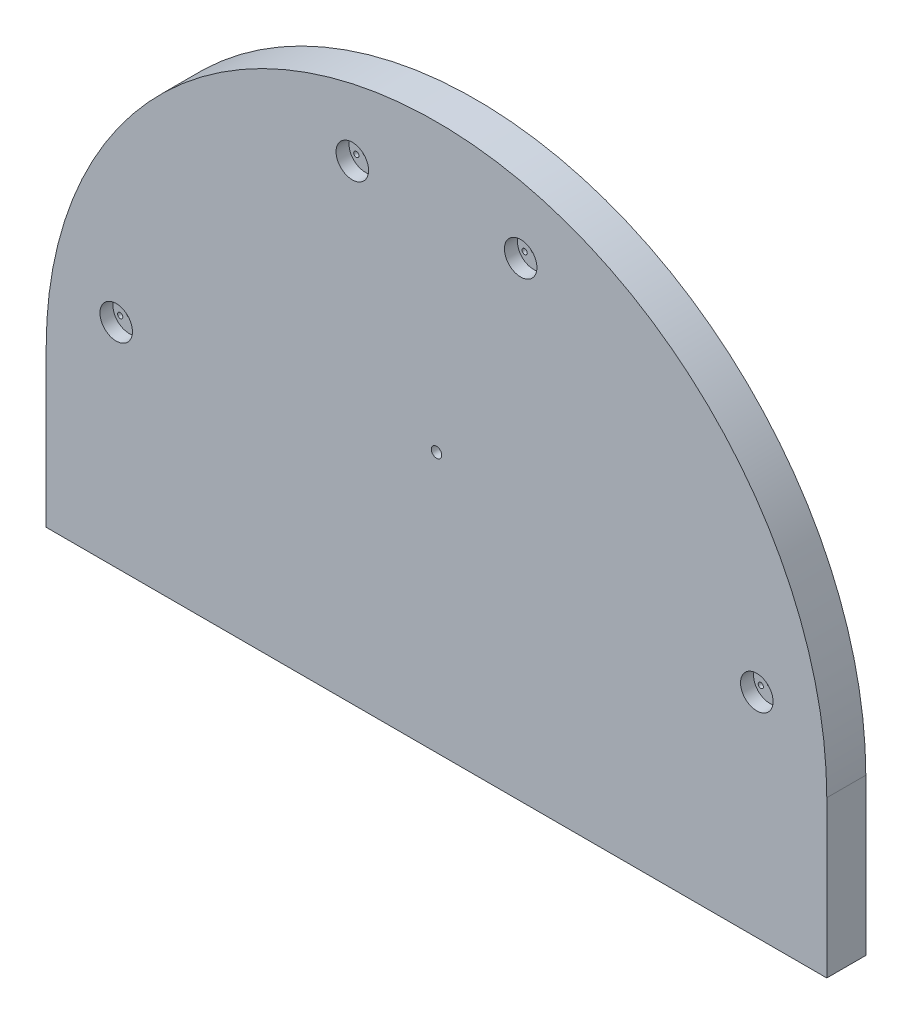
SolidWorks part; units mm, degrees
material "有机玻璃 (TM) GS 丙烯酸铸钣"
ref_plane "前视基准面" through (0, 0, 0) normal (0, 0, 1) x (1, 0, 0)
ref_plane "上视基准面" through (0, 0, 0) normal (0, 1, 0) x (1, 0, 0)
ref_plane "右视基准面" through (0, 0, 0) normal (1, 0, 0) x (0, 0, -1)
sketch "草图1" plane through (0, 0, 0) normal (0, 0, 1) x (1, 0, 0)
  line L0 (-300, 0) -> (-300, -120)
  line L1 (-300, -120) -> (300, -120)
  line L2 (300, -120) -> (300, 0)
  arc A0 (300, 0) -> (-300, 0) centre (0, 0) ccw
  dimension "D1" = 600
  dimension "D2" = 120
extrude "凸台-拉伸1" add sketch "草图1" along normal blind 30
sketch "草图2" plane through (0, 0, 30) normal (0, 0, 1) x (1, 0, 0)
  line L0 (0, 0) -> (-246.2019, 43.412) construction
  line L1 (0, 0) -> (-64.7048, 241.4815) construction
  line L2 (0, 0) -> (0, 96.9223) construction
  line L3 (0, 0) -> (-105.8449, 0) construction
  circle A0 centre (0, 0) radius 250 construction
  circle A1 centre (-246.2019, 43.412) radius 12.5
  circle A2 centre (-64.7048, 241.4815) radius 12.5
  circle A3 centre (246.2019, 43.412) radius 12.5
  circle A4 centre (64.7048, 241.4815) radius 12.5
  dimension "D1" = 500
  dimension "D4" = 25
  dimension "D5" = 25
  dimension "D2" = 15
  dimension "D3" = 10
extrude "切除-拉伸1" cut sketch "草图2" against normal blind 10
sketch "草图4" plane through (0, 0, 20) normal (0, 0, 1) x (1, 0, 0)
  line L0 (0, 0) -> (0, 96.5541) construction
  line L1 (-246.2019, 51.412) -> (-253.1301, 39.412) construction
  line L2 (-246.2019, 51.412) -> (-246.2019, 43.412) construction
  line L3 (-246.2019, 51.412) -> (-239.2737, 39.412) construction
  line L4 (-64.7048, 249.4815) -> (-64.7048, 241.4815) construction
  line L5 (-64.7048, 241.4815) -> (-71.633, 237.4815) construction
  line L6 (-64.7048, 241.4815) -> (-57.7766, 237.4815) construction
  line L7 (64.7048, 241.4815) -> (57.7766, 237.4815) construction
  line L8 (64.7048, 241.4815) -> (71.633, 237.4815) construction
  line L9 (64.7048, 249.4815) -> (64.7048, 241.4815) construction
  line L10 (246.2019, 51.412) -> (239.2737, 39.412) construction
  line L11 (246.2019, 51.412) -> (246.2019, 43.412) construction
  line L12 (246.2019, 51.412) -> (253.1301, 39.412) construction
  circle A0 centre (-246.2019, 43.412) radius 2
  circle A4 centre (-246.2019, 43.412) radius 8 construction
  circle A5 centre (-246.2019, 51.412) radius 2
  circle A6 centre (-253.1301, 39.412) radius 2
  circle A7 centre (-239.2737, 39.412) radius 2
  circle A8 centre (0, 0) radius 250 construction
  circle A9 centre (-64.7048, 241.4815) radius 8 construction
  circle A10 centre (-64.7048, 249.4815) radius 2
  circle A11 centre (-71.633, 237.4815) radius 2
  circle A12 centre (-57.7766, 237.4815) radius 2
  circle A13 centre (-64.7048, 241.4815) radius 2
  circle A14 centre (64.7048, 241.4815) radius 8 construction
  circle A15 centre (246.2019, 43.412) radius 8 construction
  circle A16 centre (64.7048, 241.4815) radius 2
  circle A17 centre (57.7766, 237.4815) radius 2
  circle A18 centre (71.633, 237.4815) radius 2
  circle A19 centre (64.7048, 249.4815) radius 2
  circle A20 centre (239.2737, 39.412) radius 2
  circle A21 centre (253.1301, 39.412) radius 2
  circle A22 centre (246.2019, 51.412) radius 2
  circle A23 centre (246.2019, 43.412) radius 2
  dimension "D1" = 4
  dimension "D4" = 16
  dimension "D5" = 4
  dimension "D6" = 4
  dimension "D7" = 4
  dimension "D8" = 16
  dimension "D11" = 4
  dimension "D2" = 30
  dimension "D3" = 30
  dimension "D9" = 120
  dimension "D10" = 120
extrude "切除-拉伸2" cut sketch "草图4" against normal blind 20
sketch "草图6" plane through (0, 0, 0) normal (0, 0, -1) x (-1, 0, 0)
  line L0 (300, -120) -> (-300, -120) construction
  circle A0 centre (0, 80) radius 4
  dimension "D1" = 200
  dimension "D2" = 8
extrude "切除-拉伸3" cut sketch "草图6" against normal blind 59
